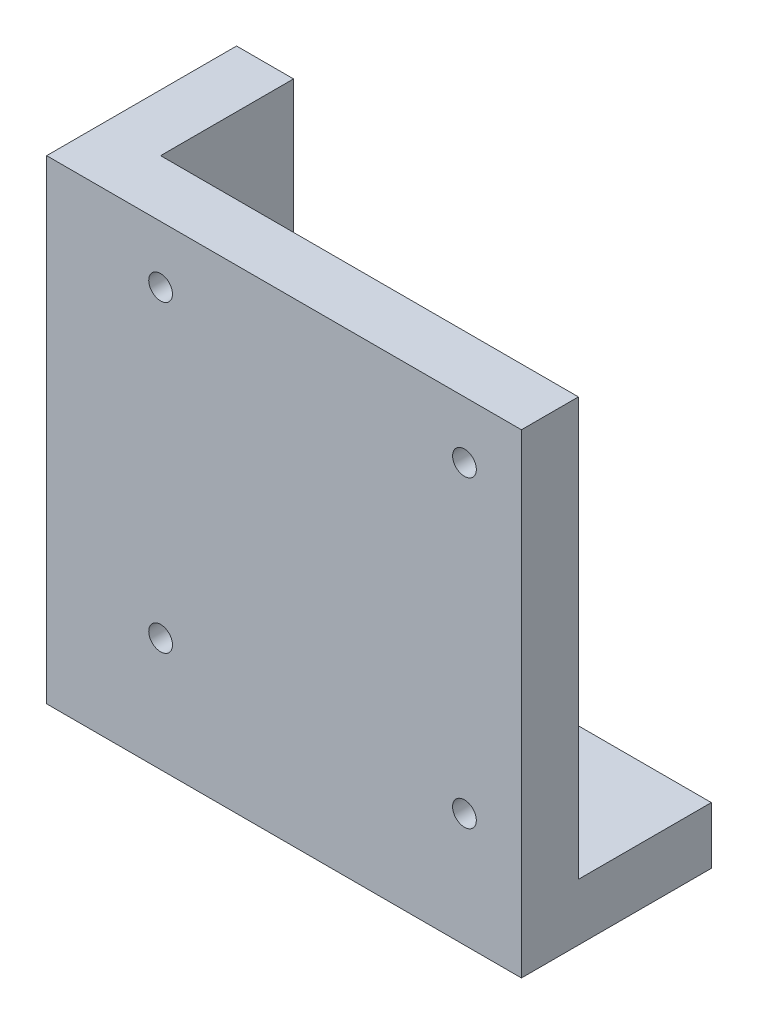
SolidWorks part; units mm, degrees
ref_plane "Front Plane" through (0, 0, 0) normal (0, 0, 1) x (1, 0, 0)
ref_plane "Top Plane" through (0, 0, 0) normal (0, 1, 0) x (1, 0, 0)
ref_plane "Right Plane" through (0, 0, 0) normal (1, 0, 0) x (0, 0, -1)
sketch "Sketch1" plane through (0, 0, 0) normal (0, 1, 0) x (1, 0, 0)
  line L1 (-21.3178, 5.6202) -> (28.6822, 5.6202)
  line L2 (-21.3178, 5.6202) -> (-21.3178, -14.3798)
  line L3 (-21.3178, -14.3798) -> (28.6822, -14.3798)
  line L4 (28.6822, 5.6202) -> (28.6822, -14.3798)
  dimension "D1" = 50
  dimension "D2" = 20
extrude "Boss-Extrude1" add sketch "Sketch1" along normal blind 6
sketch "Sketch2" plane through (0, 6, 0) normal (0, 1, 0) x (1, 0, 0)
  line L0 (-21.3178, -14.3798) -> (28.6822, -14.3798) construction
  line L1 (-21.3178, 5.6202) -> (-15.3178, 5.6202)
  line L2 (-21.3178, 5.6202) -> (-21.3178, -14.3798)
  line L3 (-21.3178, -14.3798) -> (-15.3178, -14.3798)
  line L4 (-15.3178, 5.6202) -> (-15.3178, -14.3798)
  dimension "D1" = 6
extrude "Boss-Extrude2" add sketch "Sketch2" along normal blind 44
sketch "Sketch3" plane through (0, 6, 0) normal (0, 1, 0) x (1, 0, 0)
  line L0 (-15.3178, -14.3798) -> (-15.3178, 5.6202) construction
  line L1 (28.6822, -14.3798) -> (-15.3178, -14.3798)
  line L2 (28.6822, -14.3798) -> (28.6822, -8.3798)
  line L3 (28.6822, -8.3798) -> (-15.3178, -8.3798)
  line L4 (-15.3178, -14.3798) -> (-15.3178, -8.3798)
  dimension "D1" = 6
extrude "Boss-Extrude3" add sketch "Sketch3" along normal blind 44
sketch "Sketch4" plane through (0, 0, 8.3798) normal (0, 0, -1) x (-1, 0, 0)
  line L0 (-28.6822, 50) -> (15.3178, 50) construction
  line L2 (-28.6822, 50) -> (-28.6822, 6) construction
  circle A0 centre (-22.6822, 44) radius 1.25
  circle A1 centre (9.3178, 44) radius 1.25
  circle A2 centre (-22.6822, 12) radius 1.25
  circle A3 centre (9.3178, 12) radius 1.25
  point P14 (-6.6822, 50)
  dimension "D1" = 32
  dimension "D2" = 32
  dimension "D3" = 32
  dimension "D4" = 32
  dimension "D5" = 16
  dimension "D6" = 6
  dimension "D7" = 6
extrude "Cut-Extrude1" cut sketch "Sketch4" against normal blind 44
